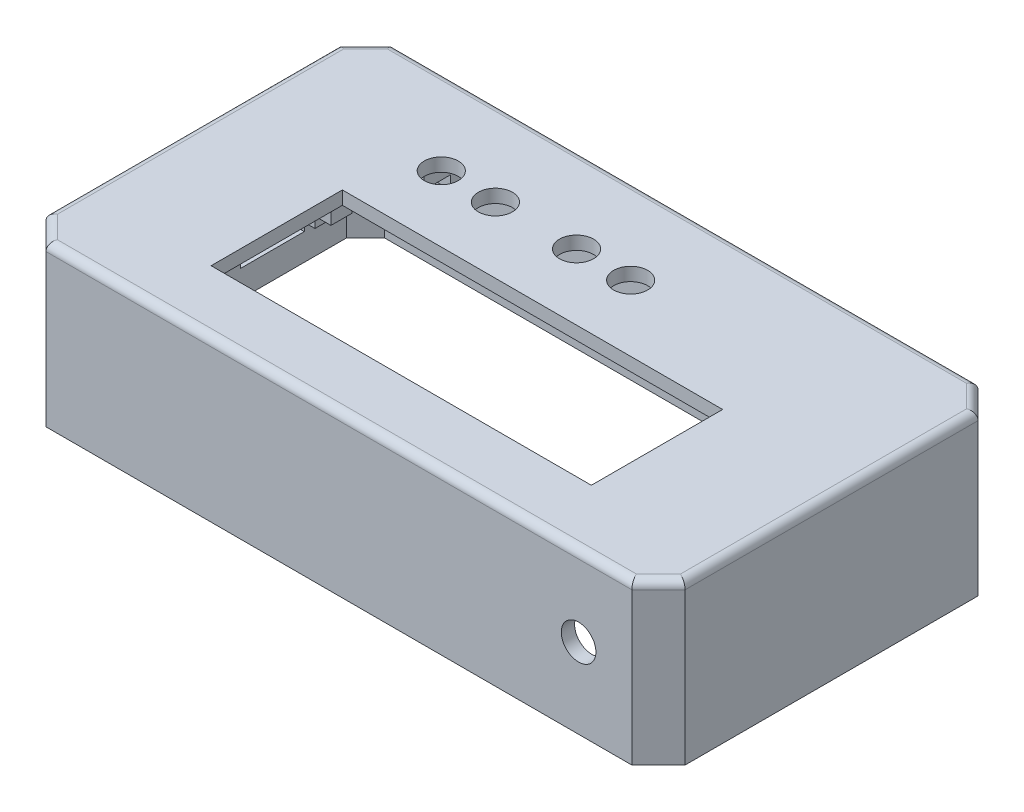
SolidWorks part; units mm, degrees
ref_plane "Front Plane" through (0, 0, 0) normal (0, 0, 1) x (1, 0, 0)
ref_plane "Top Plane" through (0, 0, 0) normal (0, 1, 0) x (1, 0, 0)
ref_plane "Right Plane" through (0, 0, 0) normal (1, 0, 0) x (0, 0, -1)
sketch "Sketch1" plane through (0, 0, 0) normal (0, 1, 0) x (1, 0, 0)
  line L0 (0, -16.5) -> (0, 16.5) construction
  line L1 (-60, 32.5) -> (60, 32.5)
  line L2 (-60, 32.5) -> (-60, -32.5)
  line L3 (-60, -32.5) -> (60, -32.5)
  line L4 (60, 32.5) -> (60, -32.5)
  line L5 (-16.5, 0) -> (16.5, 0) construction
  point P4 (0, -32.5)
  point P7 (60, 0)
  dimension "D1" = 65
  dimension "D2" = 120
extrude "Boss-Extrude1" add sketch "Sketch1" along normal blind 30 contours L1 L4 L3 L2
chamfer "Chamfer1" distance 5 angle 45 4 edges at (60, 15, -32.5) (-60, 15, -32.5) (60, 15, 32.5) (-60, 15, 32.5)
fillet "Fillet1" radius 1.5 8 edges at (57.5, 30, 30) (0, 30, 32.5) (-57.5, 30, 30) (-60, 30, 0) (-57.5, 30, -30) (0, 30, -32.5) (57.5, 30, -30) (60, 30, 0)
shell "Shell1" thickness 2.5
ref_plane "Plane1" through (0, 0, 20) normal (0, 0, 1) x (1, 0, 0)
sketch "Sketch2" plane through (0, 0, 20) normal (0, 0, 1) x (1, 0, 0)
  line L0 (47, 27.5) -> (47, 22)
  line L1 (53.9645, 27.5) -> (-53.9645, 27.5) construction
  line L2 (47, 22) -> (40, 22)
  line L3 (40, 22) -> (40, 24)
  line L4 (40, 24) -> (37, 24)
  line L5 (37, 24) -> (37, 27.5)
  line L6 (37, 27.5) -> (47, 27.5)
  line L7 (-54.3787, 30) -> (54.3787, 30) construction
  line L8 (0, -16.5) -> (0, 16.5) construction
  dimension "D1" = 10
  dimension "D2" = 7
  dimension "D3" = 6
  dimension "D4" = 40
  dimension "D5" = 2
extrude "Boss-Extrude2" add sketch "Sketch2" along normal mid plane 4
pattern_linear "LPattern1" count 2 spacing 25 along (0, 0, -1) of "Boss-Extrude2"
mirror "Mirror1" about plane through (0, 0, 0) normal (1, 0, 0) of "Boss-Extrude2", "LPattern1"
ref_plane "Plane2" through (32, 0, 0) normal (1, 0, 0) x (0, 0, -1)
sketch "Sketch3" plane through (32, 0, 0) normal (1, 0, 0) x (0, 0, -1)
  line L0 (17, 27.5) -> (17, 22)
  line L2 (17, 22) -> (10, 22)
  line L3 (10, 22) -> (10, 24)
  line L4 (10, 24) -> (7, 24)
  line L5 (7, 24) -> (7, 27.5)
  line L6 (7, 27.5) -> (17, 27.5)
  line L9 (0, 16.5) -> (0, -16.5) construction
  line L10 (-26.4645, 27.5) -> (26.4645, 27.5) construction
  line L11 (3, 24) -> (7, 24) construction
  line L12 (3, 22) -> (7, 22) construction
  line L13 (-8, 30) -> (-8, 7.6478) construction
  line L14 (-26.8787, 30) -> (26.8787, 30) construction
  line L15 (-23, 27.5) -> (-30, 27.5)
  line L16 (-23, 24) -> (-23, 27.5)
  line L17 (-26, 24) -> (-23, 24)
  line L18 (-26, 22) -> (-26, 24)
  line L19 (-30, 22) -> (-26, 22)
  line L21 (-30, 27.5) -> (-30, 22)
  line L22 (-30, 0) -> (-30, 27.5) construction
  dimension "D1" = 10
  dimension "D2" = 7
  dimension "D3" = 18
  dimension "D4" = 8
extrude "Boss-Extrude3" add sketch "Sketch3" along normal mid plane 4
sketch "Sketch4" plane through (0, 27.5, 0) normal (0, -1, 0) x (1, 0, 0)
  line L4 (-35.5, -3.65) -> (35.5, -3.65)
  line L5 (-35.5, 20.6) -> (-35.5, -3.65)
  line L6 (35.5, 20.6) -> (-35.5, 20.6)
  line L7 (35.5, -3.65) -> (35.5, 20.6)
  line L8 (-35.5, -3.65) -> (35.5, -3.65)
  line L9 (11.04, -24.716) -> (11.04, -13.286)
  line L10 (11.04, -13.286) -> (13.58, -10.746)
  line L11 (13.58, -10.746) -> (13.58, 22.02)
  line L12 (13.58, 22.02) -> (11.04, 24.56)
  line L13 (11.04, 24.56) -> (11.04, 26.1)
  line L14 (10.04, 27.1) -> (-54, 27.1)
  line L15 (-55, 26.1) -> (-55, -25.24)
  line L16 (-54, -26.24) -> (9.516, -26.24)
  line L17 (9.516, -26.24) -> (11.04, -24.716)
  line L18 (11.04, -24.716) -> (11.04, -13.286)
  line L19 (11.04, -13.286) -> (13.58, -10.746)
  line L20 (13.58, -10.746) -> (13.58, 22.02)
  line L21 (13.58, 22.02) -> (11.04, 24.56)
  line L22 (11.04, 24.56) -> (11.04, 26.1)
  line L23 (10.04, 27.1) -> (-54, 27.1)
  line L24 (-55, 26.1) -> (-55, -25.24)
  line L25 (-54, -26.24) -> (9.516, -26.24)
  line L26 (9.516, -26.24) -> (11.04, -24.716)
  line L27 (-35.5, 20.6) -> (-35.5, -3.65)
  line L28 (35.5, 20.6) -> (-35.5, 20.6)
  line L29 (35.5, -3.65) -> (35.5, 20.6)
  circle A0 centre (-39.76, -23.7) radius 1.6 construction
  circle A1 centre (6.04, -16.24) radius 3 construction
  circle A2 centre (-4.12, -16.24) radius 3 construction
  arc A3 (11.04, 26.1) -> (10.04, 27.1) centre (10.04, 26.1) ccw
  arc A4 (-54, 27.1) -> (-55, 26.1) centre (-54, 26.1) ccw
  arc A5 (-55, -25.24) -> (-54, -26.24) centre (-54, -25.24) ccw
  arc A6 (11.04, 26.1) -> (10.04, 27.1) centre (10.04, 26.1) ccw
  arc A7 (-54, 27.1) -> (-55, 26.1) centre (-54, 26.1) ccw
  arc A8 (-55, -25.24) -> (-54, -26.24) centre (-54, -25.24) ccw
  circle A9 centre (-19.36, -16.24) radius 3 construction
  circle A10 centre (-29.52, -16.24) radius 3 construction
  circle A11 centre (-39.76, -23.7) radius 1.6
  circle A12 centre (6.04, -16.24) radius 3
  circle A13 centre (-4.12, -16.24) radius 3
  circle A14 centre (-19.36, -16.24) radius 3
  circle A15 centre (-29.52, -16.24) radius 3
  dimension "D1" = 0
  dimension "D2" = 0
ref_plane "Plane3" through (-39.76, 0, 0) normal (1, 0, 0) x (0, 0, -1)
sketch "Sketch5" plane through (-39.76, 0, 0) normal (1, 0, 0) x (0, 0, -1)
  line L0 (21.24, 27.5) -> (21.24, 20.25)
  line L1 (22.1, 27.5) -> (25.3, 27.5) construction
  line L2 (21.24, 20.25) -> (26.24, 20.25)
  line L3 (26.24, 20.25) -> (26.24, 17.75)
  line L4 (26.24, 17.75) -> (30, 17.75)
  line L5 (30, 27.5) -> (30, 0) construction
  line L6 (30, 17.75) -> (30, 27.5)
  line L7 (26.4645, 27.5) -> (30, 27.5) construction
  line L8 (26.24, 27.5) -> (26.24, 23.3986) construction
  line L9 (7, 24) -> (10, 24) construction
  line L10 (25.24, 27.5) -> (26.24, 27.5) construction
  line L11 (-26.4645, 27.5) -> (26.4645, 27.5) construction
  line L12 (21.24, 27.5) -> (30, 27.5)
  dimension "D1" = 3.75
  dimension "D2" = 2.5
  dimension "D3" = 5
extrude "Boss-Extrude4" add sketch "Sketch5" along normal mid plane 4
sketch "Sketch6" plane through (0, 30, 0) normal (0, 1, 0) x (1, 0, 0)
  line L38 (35.7, -20.8) -> (35.7, 3.85)
  line L39 (-35.7, -20.8) -> (35.7, -20.8)
  line L40 (-35.7, 3.85) -> (-35.7, -20.8)
  line L41 (35.7, 3.85) -> (-35.7, 3.85)
  line L42 (35.7, -20.8) -> (35.7, 3.85)
  line L43 (-35.7, -20.8) -> (35.7, -20.8)
  line L44 (-35.7, 3.85) -> (-35.7, -20.8)
  line L45 (35.7, 3.85) -> (-35.7, 3.85)
  circle A38 centre (-29.52, 16.24) radius 3.2
  circle A39 centre (-29.52, 16.24) radius 3.2
  circle A41 centre (-19.36, 16.24) radius 3.2
  circle A42 centre (-19.36, 16.24) radius 3.2
  circle A44 centre (-4.12, 16.24) radius 3.2
  circle A45 centre (-4.12, 16.24) radius 3.2
  circle A47 centre (6.04, 16.24) radius 3.2
  circle A48 centre (6.04, 16.24) radius 3.2
  dimension "D1" = 0.2
  dimension "D2" = 0.2
  dimension "D3" = 0.2
  dimension "D4" = 0.2
  dimension "D5" = 0.2
sketch "Sketch7" plane through (-60, 0, 0) normal (-1, 0, 0) x (0, 0, 1)
  line L0 (-16.056, 7.5) -> (-8.944, 7.5) construction
  line L1 (-16.056, 10.5) -> (-16.056, 7.5) construction
  line L2 (-16.056, 10.5) -> (-8.944, 10.5) construction
  line L3 (-8.944, 10.5) -> (-8.944, 7.5) construction
  line L4 (-16.056, 7.5) -> (-8.944, 7.5) construction
  line L5 (-16.056, 10.5) -> (-16.056, 7.5) construction
  line L6 (-16.056, 10.5) -> (-8.944, 10.5) construction
  line L7 (-8.944, 10.5) -> (-8.944, 7.5) construction
  line L8 (-8.944, 10.5) -> (-16.056, 7.5) construction
  line L10 (-18.5, 13) -> (-6.5, 13)
  line L11 (-18.5, 13) -> (-18.5, 5)
  line L12 (-18.5, 5) -> (-6.5, 5)
  line L13 (-6.5, 13) -> (-6.5, 5)
  line L14 (-18.5, 13) -> (-6.5, 5) construction
  line L15 (-18.5, 5) -> (-6.5, 13) construction
  circle A0 centre (19.3022, 14) radius 1 construction
  circle A1 centre (19.3022, 14) radius 1 construction
  circle A2 centre (19.3022, 14) radius 6
  point P8 (-12.5, 9)
  dimension "D1" = 12
  dimension "D2" = 12
  dimension "D3" = 8
extrude "Cut-Extrude1" cut sketch "Sketch7" against normal up to next
sketch "Sketch8" plane through (0, 0, -32.5) normal (0, 0, -1) x (-1, 0, 0)
  line L0 (55, 0) -> (-55, 0) construction
  line L2 (-48, 6) -> (-48, 0)
  line L3 (-42, 6) -> (-42, 0)
  line L4 (-60, 0) -> (-60, 28.5) construction
  arc A0 (-42, 6) -> (-48, 6) centre (-45, 6) ccw
  dimension "D1" = 6
  dimension "D2" = 6
  dimension "D3" = 15
extrude "Cut-Extrude3" cut sketch "Sketch8" against normal blind 10 and the other way through all flip side to cut
sketch "Sketch9" plane through (0, 0, 32.5) normal (0, 0, 1) x (1, 0, 0)
  line L0 (60, 28.5) -> (60, 0) construction
  line L1 (35.75, 0) -> (-35.75, 0) construction
  circle A1 centre (45, 15) radius 3.25
  dimension "D1" = 6.5
  dimension "D2" = 15
  dimension "D3" = 15
extrude "Cut-Extrude4" cut sketch "Sketch9" against normal blind 10
extrude "Cut-Extrude5" cut sketch "Sketch6" against normal blind 10
